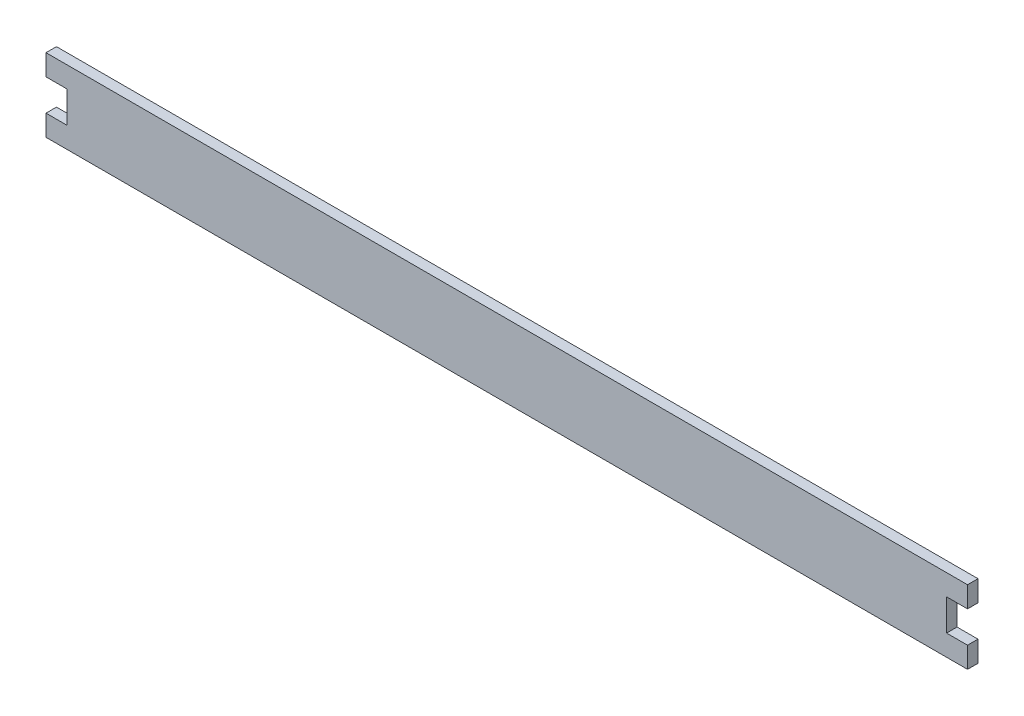
SolidWorks part; units mm, degrees
ref_plane "Front Plane" through (0, 0, 0) normal (0, 0, 1) x (1, 0, 0)
ref_plane "Top Plane" through (0, 0, 0) normal (0, 1, 0) x (1, 0, 0)
ref_plane "Right Plane" through (0, 0, 0) normal (1, 0, 0) x (0, 0, -1)
sketch "Sketch1" plane through (0, 0, 0) normal (0, 0, 1) x (1, 0, 0)
  line L0 (-1.5438, -155.8637) -> (-1.5438, -275.8637) construction
  line L6 (-1.5438, -233.3637) -> (8.4562, -233.3637)
  line L7 (8.4562, -208.3637) -> (-1.5438, -208.3637)
  line L8 (428.4562, -233.3637) -> (438.4562, -233.3637)
  line L10 (428.4562, -218.3637) -> (438.4562, -218.3637)
  line L12 (428.4562, -208.3637) -> (438.4562, -208.3637)
  line L13 (438.4562, -208.3637) -> (438.4562, -218.3637)
  line L14 (-1.5438, -208.3637) -> (-1.5438, -218.3637)
  line L15 (360.9886, -430) -> (346.3445, -430) construction
  line L16 (428.4562, -243.3637) -> (438.4562, -243.3637)
  line L17 (8.4562, -218.3637) -> (-1.5438, -218.3637)
  line L18 (438.4562, -233.3637) -> (428.4562, -233.3637)
  line L19 (428.4562, -243.3637) -> (8.4562, -243.3637)
  line L20 (438.4562, -155.8637) -> (438.4562, -275.8637) construction
  line L21 (-1.5438, -233.3637) -> (-1.5438, -243.3637)
  line L22 (-1.5438, -243.3637) -> (8.4562, -243.3637)
  line L23 (8.4562, -218.3637) -> (8.4562, -233.3637)
  line L24 (438.4562, -243.3637) -> (438.4562, -233.3637)
  line L25 (428.4562, -233.3637) -> (428.4562, -218.3637)
  line L30 (428.4562, -208.3637) -> (8.4562, -208.3637)
  point P1 (225, -254.86)
  point P2 (410, -231.9343)
  point P18 (40, -231.9343)
  point P31 (40, -247.7858)
  point P32 (410, -247.7858)
  point P33 (225, -224.86)
  dimension "D1" = 10
  dimension "D2" = 10
  dimension "D3" = 15
  dimension "D4" = 10
  dimension "D5" = 10
  dimension "D6" = 15
  dimension "D7" = 10
  dimension "D8" = 10
extrude "Boss-Extrude1" add sketch "Sketch1" against normal blind 5
